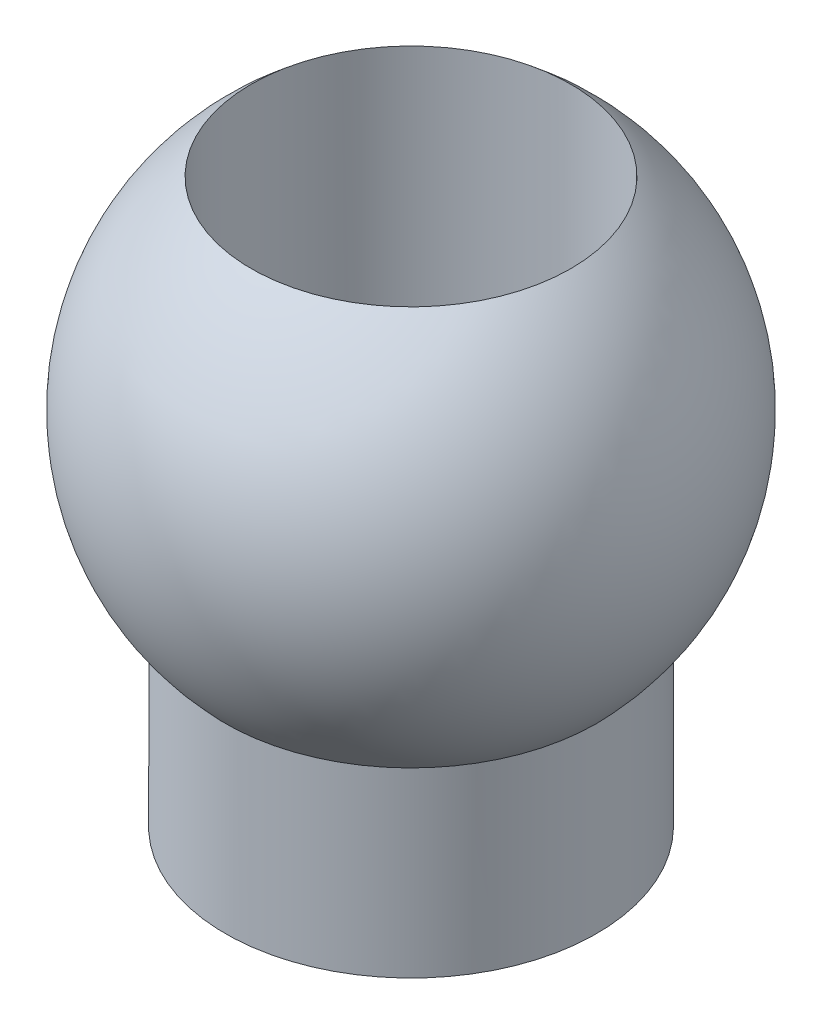
SolidWorks part; units mm, degrees
ref_plane "Plan de face" through (0, 0, 0) normal (0, 0, 1) x (1, 0, 0)
ref_plane "Plan de dessus" through (0, 0, 0) normal (0, 1, 0) x (1, 0, 0)
ref_plane "Plan de droite" through (0, 0, 0) normal (1, 0, 0) x (0, 0, -1)
sketch "Esquisse1" plane through (0, 0, 0) normal (0, 0, 1) x (1, 0, 0)
  line L0 (0, 0) -> (0, 6)
  line L1 (1.8, 0) -> (1.8, 1.7651)
  line L2 (0, 0) -> (1.8, 0)
  arc A0 (0, 6) -> (1.8, 1.7651) centre (0, 3.5) cw
  dimension "D1" = 6
  dimension "D2" = 2.5
  dimension "D3" = 1.8
revolve "Révolution1" add sketch "Esquisse1" angle 360 about L0
sketch "Esquisse2" plane through (0, 0, 0) normal (0, 1, 0) x (1, 0, 0)
  circle A0 centre (0, 0) radius 1.55
  dimension "D1" = 3.1
extrude "Enlèv. mat.-Extru.1" cut sketch "Esquisse2" against normal through all both and the other way through all
